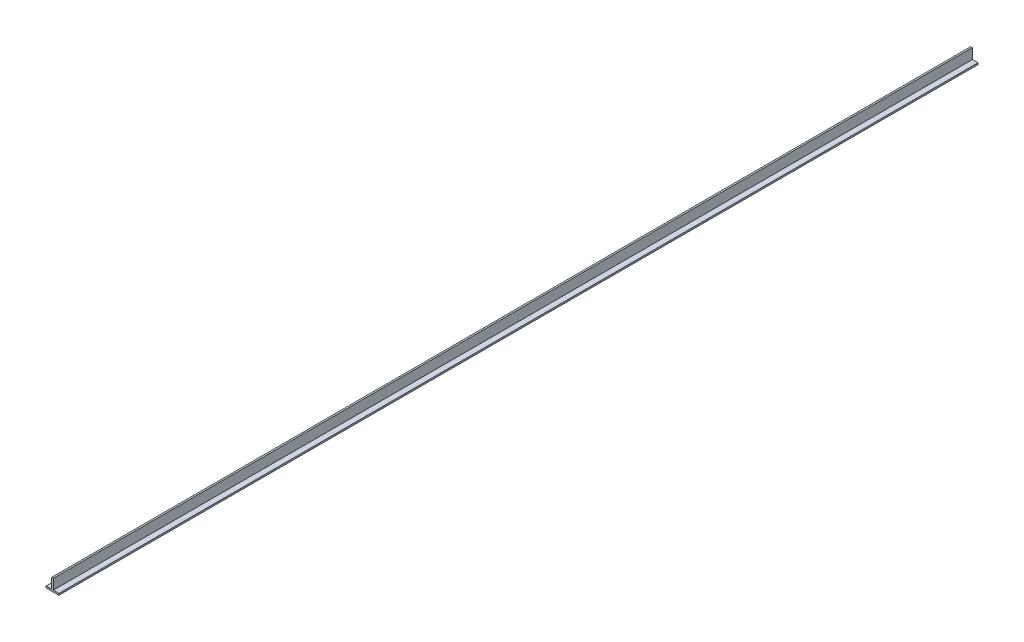
SolidWorks part; units mm, degrees
ref_plane "Front Plane" through (0, 0, 0) normal (0, 0, 1) x (1, 0, 0)
ref_plane "Top Plane" through (0, 0, 0) normal (0, 1, 0) x (1, 0, 0)
ref_plane "Right Plane" through (0, 0, 0) normal (1, 0, 0) x (0, 0, -1)
sketch "Sketch1" plane through (0, 0, 0) normal (0, 0, 1) x (1, 0, 0)
  line L0 (4.5, 65) -> (-4.5, 65)
  line L1 (-4.5, 65) -> (-4.5, 9)
  line L2 (-4.5, 9) -> (-35, 9)
  line L3 (-35, 9) -> (-35, 0)
  line L4 (-35, 0) -> (35, 0)
  line L5 (0, 65) -> (0, 0) construction
  line L6 (35, 9) -> (35, 0)
  line L7 (4.5, 9) -> (35, 9)
  line L8 (4.5, 65) -> (4.5, 9)
  dimension "D1" = 4.5
  dimension "D2" = 65
  dimension "D3" = 9
  dimension "D4" = 35
extrude "Boss-Extrude1" add sketch "Sketch1" along normal blind 5000
